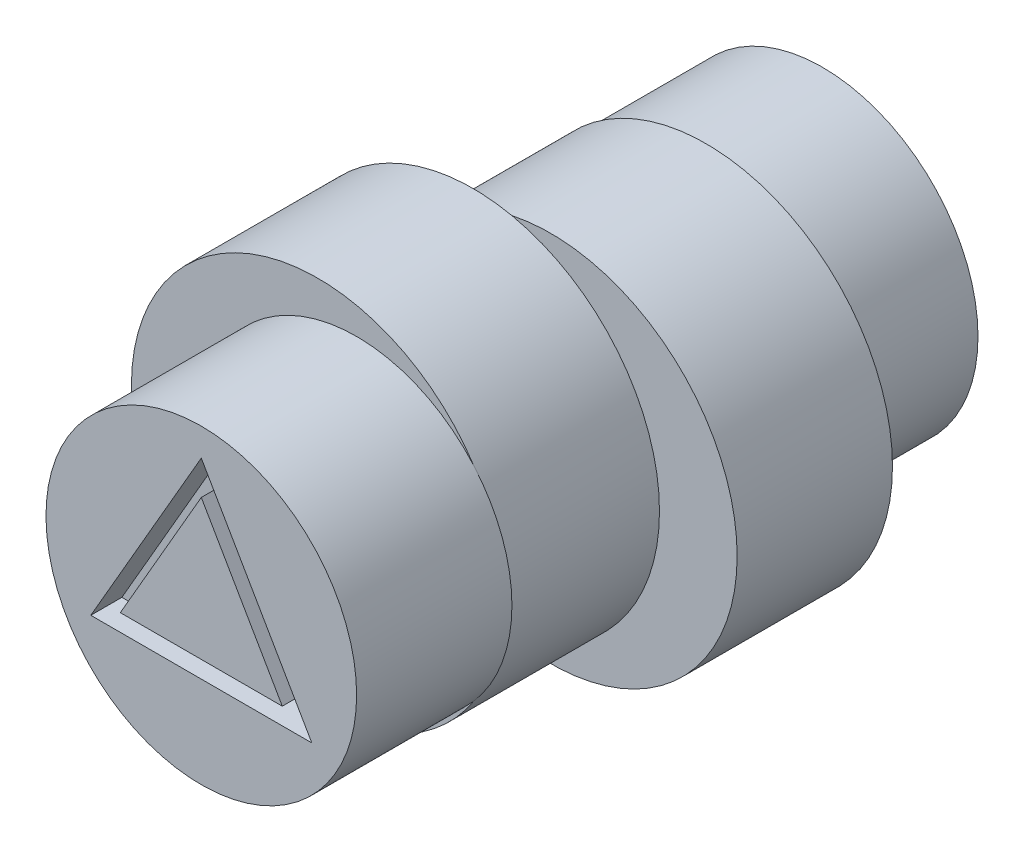
SolidWorks part; units mm, degrees
ref_plane "Front Plane" through (0, 0, 0) normal (0, 0, 1) x (1, 0, 0)
ref_plane "Top Plane" through (0, 0, 0) normal (0, 1, 0) x (1, 0, 0)
ref_plane "Right Plane" through (0, 0, 0) normal (1, 0, 0) x (0, 0, -1)
sketch "Sketch2" plane through (0, 0, -1161.5823) normal (0, 0, 1) x (1, 0, 0)
  line L0 (2, 1.5) -> (2, -1.5)
  arc A0 (2, 1.5) -> (2, -1.5) centre (0, 0) ccw
  circle A1 centre (0, 0) radius 5.0038
extrude "Boss-Extrude1" add sketch "Sketch2" along normal up to surface (5 mm away)
sketch "Sketch3" plane through (0, 0, -1156.5823) normal (0, 0, 1) x (1, 0, 0)
  line L0 (2, 1.5) -> (2, -1.5)
  circle A0 centre (1.25, 0) radius 6
  arc A1 (2, 1.5) -> (2, -1.5) centre (0, 0) ccw
  point P0 (1.25, 0)
extrude "Boss-Extrude2" add sketch "Sketch3" along normal blind 5
sketch "Sketch5" plane through (0, 0, -1151.5823) normal (0, 0, 1) x (1, 0, 0)
  line L0 (2, 1.5) -> (2, -1.5)
  arc A1 (2, 1.5) -> (2, -1.5) centre (0, 0) ccw
  circle A3 centre (-1.25, 0) radius 6
  point P0 (-1.25, 0)
extrude "Boss-Extrude3" add sketch "Sketch5" along normal blind 5
sketch "Sketch6" plane through (0, 0, -1146.5823) normal (0, 0, 1) x (1, 0, 0)
  line L0 (2, 1.5) -> (2, -1.5)
  circle A0 centre (0, 0) radius 5
  arc A1 (2, 1.5) -> (2, -1.5) centre (0, 0) ccw
extrude "Boss-Extrude4" add sketch "Sketch6" along normal blind 5
sketch "Sketch8" plane through (0, 0, -1146.1823) normal (0, 0, 1) x (1, 0, 0)
  circle A1 centre (0, 0) radius 2.6981
extrude "Boss-Extrude5" add sketch "Sketch8" along normal up to surface (4.6 mm away) up to face at (5, 0, -1141.5823)
sketch "Sketch9" plane through (0, 0, -1141.5823) normal (0, 0, 1) x (1, 0, 0)
  line L4 (0, 4.1076) -> (-3.5573, -2.0538)
  line L5 (-3.5573, -2.0538) -> (3.5573, -2.0538)
  line L6 (3.5573, -2.0538) -> (0, 4.1076)
  line L7 (0, 3.0106) -> (-2.6072, -1.5053)
  line L8 (-2.6072, -1.5053) -> (2.6072, -1.5053)
  line L9 (2.6072, -1.5053) -> (0, 3.0106)
  circle A0 centre (0, 0) radius 2.0538 construction
  circle A1 centre (0, 0) radius 1.5053 construction
extrude "Cut-Extrude1" cut sketch "Sketch9" against normal blind 1
